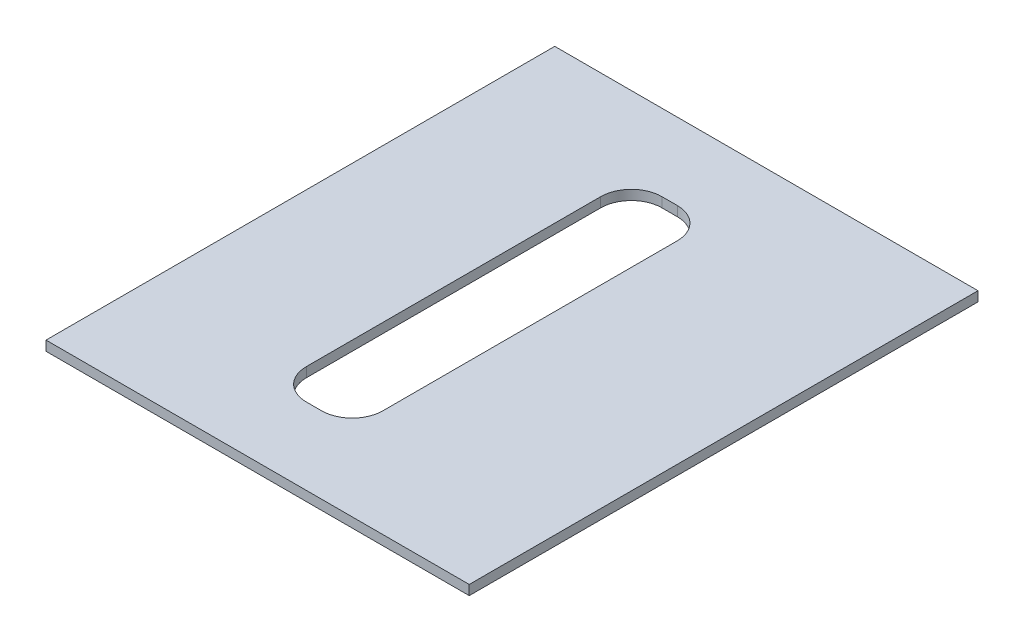
SolidWorks part; units mm, degrees
material "Acrylic (Medium-high impact)"
ref_plane "Front Plane" through (0, 0, 0) normal (0, 0, 1) x (1, 0, 0)
ref_plane "Top Plane" through (0, 0, 0) normal (0, 1, 0) x (1, 0, 0)
ref_plane "Right Plane" through (0, 0, 0) normal (1, 0, 0) x (0, 0, -1)
sketch "Sketch1" plane through (0, 0, 0) normal (0, 1, 0) x (1, 0, 0)
  line L1 (0, 0) -> (138.2, 0)
  line L2 (0, 0) -> (0, 166.124)
  line L3 (0, 166.124) -> (138.2, 166.124)
  line L4 (138.2, 0) -> (138.2, 166.124)
  line L5 (60, 141.124) -> (65, 141.124)
  line L6 (50, 131.124) -> (50, 35)
  line L7 (60, 25) -> (65, 25)
  line L8 (75, 131.124) -> (75, 35)
  arc A0 (50, 35) -> (60, 25) centre (60, 35) ccw
  arc A1 (65, 25) -> (75, 35) centre (65, 35) ccw
  arc A2 (65, 141.124) -> (75, 131.124) centre (65, 131.124) cw
  arc A3 (60, 141.124) -> (50, 131.124) centre (60, 131.124) ccw
  dimension "D7" = 10
  dimension "D1" = 138.2
  dimension "D2" = 166.124
  dimension "D3" = 50
  dimension "D4" = 25
  dimension "D5" = 25
  dimension "D6" = 25
extrude "Boss-Extrude1" add sketch "Sketch1" along normal blind 3.175
